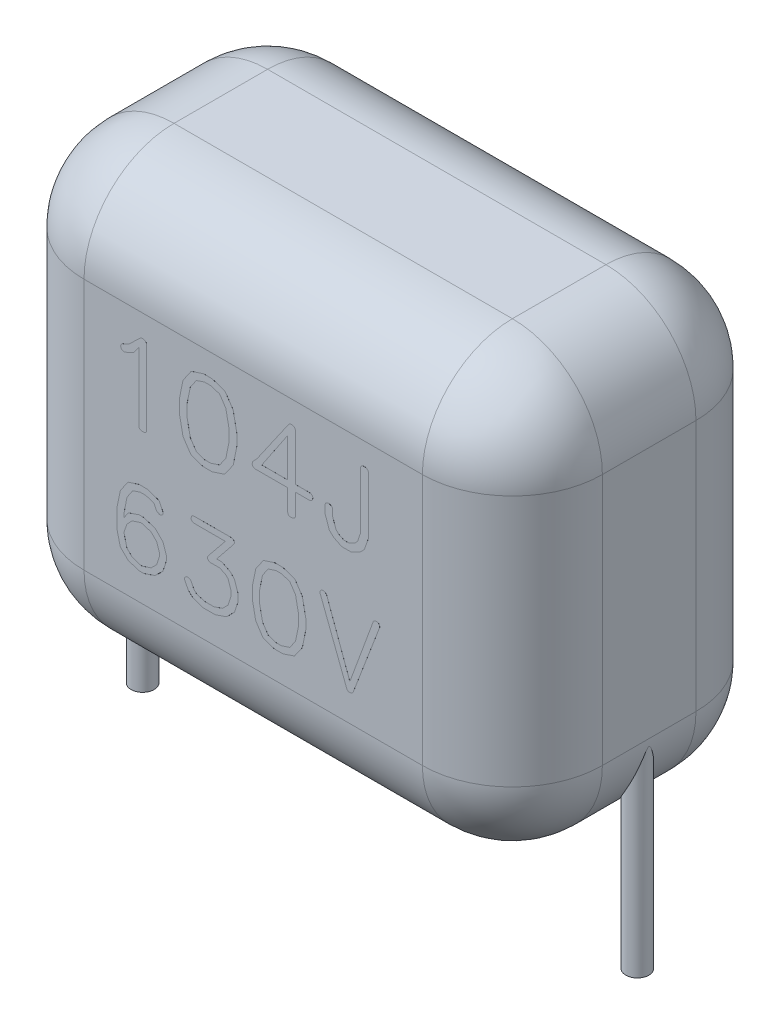
SolidWorks part; units mm, degrees
ref_plane "Front Plane" through (0, 0, 0) normal (0, 0, 1) x (1, 0, 0)
ref_plane "Top Plane" through (0, 0, 0) normal (0, 1, 0) x (1, 0, 0)
ref_plane "Right Plane" through (0, 0, 0) normal (1, 0, 0) x (0, 0, -1)
sketch "Sketch2" plane through (0, 0, 0) normal (1, 0, 0) x (0, 0, -1)
  line L0 (0, 12.4597) -> (0, -8.4662) construction
  line L2 (-1.625, 7.5) -> (1.625, 7.5)
  line L3 (-4.75, 4.375) -> (-4.75, -4.375)
  line L4 (-1.625, -7.5) -> (1.625, -7.5)
  line L5 (4.75, 4.375) -> (4.75, -4.375)
  line L6 (-4.75, 7.5) -> (4.75, -7.5) construction
  line L7 (-4.75, -7.5) -> (4.75, 7.5) construction
  arc A0 (-4.75, -4.375) -> (-1.625, -7.5) centre (-1.625, -4.375) ccw
  arc A1 (4.75, -4.375) -> (1.625, -7.5) centre (1.625, -4.375) cw
  arc A2 (4.75, 4.375) -> (1.625, 7.5) centre (1.625, 4.375) ccw
  arc A3 (-4.75, 4.375) -> (-1.625, 7.5) centre (-1.625, 4.375) cw
  point P3 (0, 0)
  dimension "D3" = 3.125
  dimension "D1" = 15
  dimension "D2" = 9.5
extrude "Boss-Extrude1" add sketch "Sketch2" along normal mid plane 18
fillet "Fillet1" radius 3.125 16 edges at (-9, -7.5, 0) (-9, -6.5847, -3.8347) (-9, 0, -4.75) (-9, 6.5847, -3.8347) (-9, 7.5, 0) (-9, 6.5847, 3.8347) (-9, 0, 4.75) (-9, -6.5847, 3.8347) (9, 0, 4.75) (9, 6.5847, 3.8347) (9, 7.5, 0) (9, 6.5847, -3.8347) (9, 0, -4.75) (9, -6.5847, -3.8347) (9, -7.5, 0) (9, -6.5847, 3.8347)
sketch "Sketch3" plane through (0, 0, 0) normal (0, 0, 1) x (1, 0, 0)
  line L0 (-5.875, 0.875) -> (5.875, 0.875) construction
  line L1 (-5.875, 4.375) -> (-5.875, -4.375) construction
  line L2 (5.875, -4.375) -> (5.875, 4.375) construction
  line L3 (-5.875, -3.375) -> (5.875, -3.375) construction
  line L4 (5.875, -4.375) -> (-5.875, -4.375) construction
  line L5 (5.875, 4.375) -> (-5.875, 4.375) construction
  text T0 "104J" font "SWSimp" height 2.8
  text T1 "630V" font "SWSimp" height 2.6
  dimension "D1" = 1
  dimension "D2" = 3.5
extrude "Boss-Extrude2" add sketch "Sketch3" along normal blind 0.001 from surface at 4.75 starting at face at (0, 0, 4.75)
sketch "Sketch4" plane through (0, 0, 0) normal (0, 1, 0) x (1, 0, 0)
  line L0 (0, 6.5305) -> (0, -6.6049) construction
  line L1 (-9, -1.625) -> (-9, 1.625) construction
  circle A0 centre (-8.59, 0) radius 0.4
  circle A1 centre (8.59, 0) radius 0.4
  dimension "D1" = 0.41
  dimension "D2" = 0.8
extrude "Boss-Extrude3" add sketch "Sketch4" against normal blind 14.5
sketch "Sketch5" plane through (0, 0, 0) normal (0, 0, 1) x (1, 0, 0)
  line L0 (5.875, -7.5) -> (-5.875, -7.5) construction
  line L1 (-11.2766, -11.5) -> (13.5418, -11.5)
  line L2 (-11.2766, -11.5) -> (-11.2766, -17.0891)
  line L3 (-11.2766, -17.0891) -> (13.5418, -17.0891)
  line L4 (13.5418, -11.5) -> (13.5418, -17.0891)
  dimension "D1" = 4
extrude "Cut-Extrude1" cut sketch "Sketch5" against normal through all both and the other way through all
